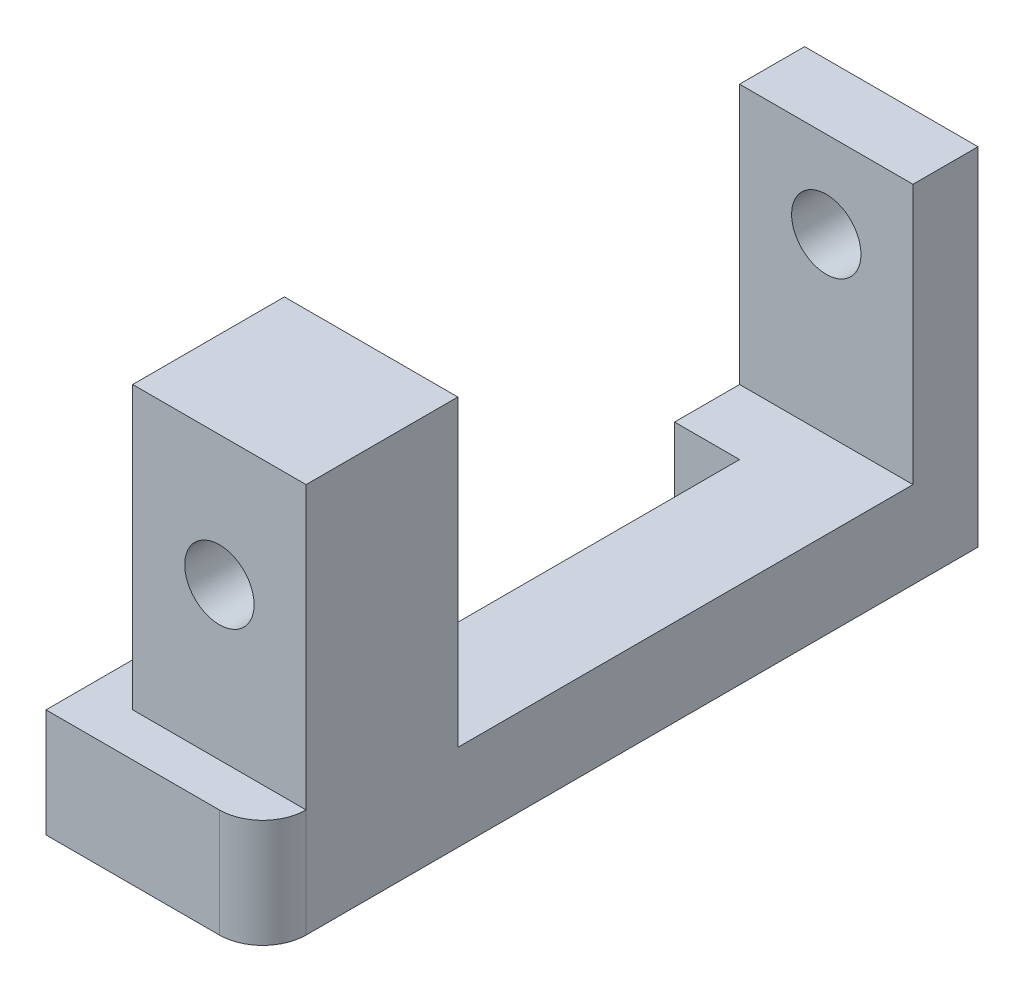
SolidWorks part; units mm, degrees
ref_plane "Front Plane" through (0, 0, 0) normal (0, 0, 1) x (1, 0, 0)
ref_plane "Top Plane" through (0, 0, 0) normal (0, 1, 0) x (1, 0, 0)
ref_plane "Right Plane" through (0, 0, 0) normal (1, 0, 0) x (0, 0, -1)
sketch "Sketch1" plane through (0, 0, 0) normal (1, 0, 0) x (0, 0, -1)
  line L0 (0, 0) -> (0, 16)
  line L1 (0, 16) -> (-3, 16)
  line L2 (-3, 16) -> (-3, 4)
  line L3 (-3, 4) -> (-24, 4)
  line L4 (-24, 4) -> (-24, 18)
  line L5 (-24, 18) -> (-31, 18)
  line L6 (-31, 18) -> (-31, 0)
  line L7 (-31, 0) -> (0, 0)
  dimension "D1" = 3
  dimension "D2" = 16
  dimension "D3" = 12
  dimension "D4" = 18
  dimension "D5" = 31
  dimension "D6" = 7
extrude "Boss-Extrude1" add sketch "Sketch1" against normal blind 8
sketch "Sketch3" plane through (-8, 0, 0) normal (-1, 0, 0) x (0, 0, 1)
  line L0 (3, 16) -> (3, 4) construction
  line L1 (3, 4) -> (24, 4)
  line L2 (3, 4) -> (3, 0)
  line L3 (3, 0) -> (24, 0)
  line L4 (24, 4) -> (24, 0)
  line L5 (24, 4) -> (24, 18) construction
  line L6 (31, 0) -> (0, 0) construction
  line L7 (3, 4) -> (24, 4) construction
extrude "Cut-Extrude1" [suppressed] cut sketch "Sketch3" against normal blind 4
sketch "Sketch5" plane through (0, 0, 3) normal (0, 0, 1) x (1, 0, 0)
  line L0 (-8, 0) -> (-3, 0)
  line L1 (-8, 0) -> (0, 0) construction
  line L2 (-3, 0) -> (-5, 4)
  line L3 (-5, 4) -> (-8, 4)
  line L4 (-8, 18) -> (-8, 0) construction
  line L5 (-8, 4) -> (-8, 0)
  dimension "D1" = 5
  dimension "D2" = 3
  dimension "D3" = 4
extrude "Cut-Extrude2" cut sketch "Sketch5" along normal up to surface (21 mm away) up to face at (-4, 11, 24)
sketch "Sketch6" plane through (0, 0, 31) normal (0, 0, 1) x (1, 0, 0)
  line L0 (0, 18) -> (0, 0) construction
  line L1 (-8, 0) -> (0, 0) construction
  circle A0 centre (-4, 12) radius 1.6
  dimension "D1" = 3.2
  dimension "D2" = 4
  dimension "D3" = 12
sketch "Sketch8" plane through (0, 0, 3) normal (0, 0, 1) x (1, 0, 0)
  line L0 (-8, 4) -> (-5, 4)
  line L1 (-5, 4) -> (-3, 0)
  line L2 (-3, 0) -> (-8, 0)
  line L3 (-8, 0) -> (-8, 4)
extrude "Boss-Extrude2" add sketch "Sketch8" along normal blind 3
sketch "Sketch11" plane through (0, 0, 0) normal (0, -1, 0) x (1, 0, 0)
  line L0 (-3, 24) -> (-8, 24) construction
  line L2 (-10, 26) -> (-10, 33)
  line L3 (-10, 33) -> (-2, 33)
  line L4 (0, 31) -> (-8, 31)
  line L5 (-8, 31) -> (-8, 24)
  line L6 (-8, 31) -> (0, 31) construction
  line L7 (0, 31) -> (0, 0) construction
  arc A0 (-2, 33) -> (0, 31) centre (-2, 31) cw
  arc A1 (-10, 26) -> (-8, 24) centre (-8, 26) ccw
  dimension "D1" = 2
  dimension "D2" = 2
extrude "Boss-Extrude5" add sketch "Sketch11" against normal blind 5
extrude "Cut-Extrude3" cut sketch "Sketch6" against normal through all
hole_wizard "Ø3.0mm Dowel Hole1" positions "Sketch12" profile "Sketch13" hole size "Ø3.0" standard "ANSI Metric"
sketch "Sketch12" plane through (0, 0, 0) normal (0, -1, 0) x (-1, 0, 0)
  line L0 (2, -33) -> (10, -33) construction
  line L1 (0, -31) -> (0, 0) construction
  point P0 (5.715, -29)
  dimension "D1" = 4
  dimension "D2" = 5.715
sketch "Sketch13" plane through (-5.715, 0, 29) normal (1, 0, 0) x (0, 0, -1)
  line L0 (0, 0) -> (0, 5.9013)
  line L1 (0, 5.9013) -> (1.5, 5)
  line L2 (1.5, 5) -> (1.5, 0)
  line L5 (1.5, 0) -> (0, 0)
  line L10 (0, 5.9013) -> (-1.5, 5) construction
  line L11 (0, -6.35) -> (0, 107.95) construction
  dimension "Hole Dia." = 3
  dimension "Hole Depth" = 5
  dimension "Drill Angle" = 118
